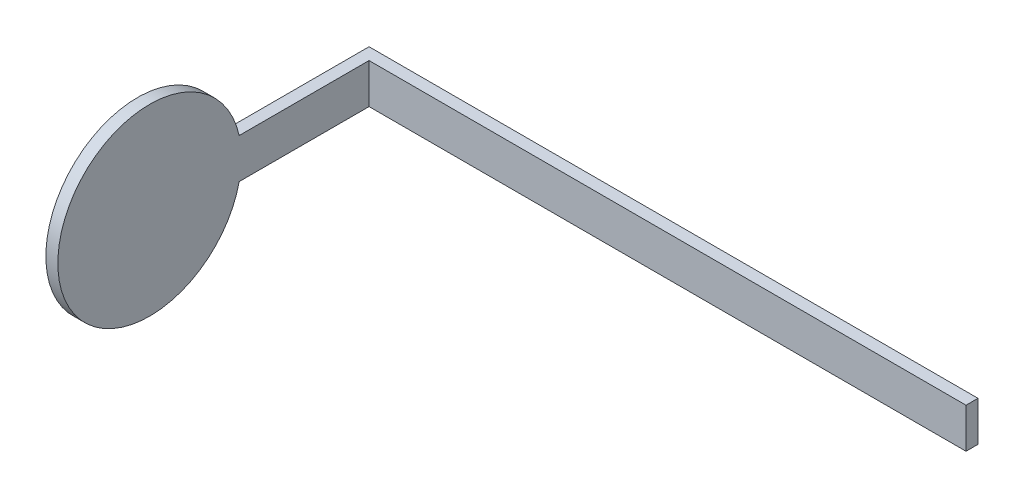
SolidWorks part; units mm, degrees
ref_plane "Спереди" through (0, 0, 0) normal (0, 0, 1) x (1, 0, 0)
ref_plane "Сверху" through (0, 0, 0) normal (0, 1, 0) x (1, 0, 0)
ref_plane "Справа" through (0, 0, 0) normal (1, 0, 0) x (0, 0, -1)
ref_plane "Плоскость4"
sketch "Эскиз1" plane through (0, 0, 0) normal (0, 1, 0) x (-1, 0, 0)
  line L0 (0, 0) -> (0, -3)
  line L1 (0, -3) -> (152.615, -3)
  line L2 (152.615, -3) -> (152.615, 60)
  line L3 (152.615, 60) -> (149.615, 60)
  line L4 (149.615, 60) -> (149.615, 0)
  line L5 (149.615, 0) -> (0, 0)
  dimension "D1" = 149.615
  dimension "D2" = 3
  dimension "D3" = 60
extrude "Выдавливание2" add sketch "Эскиз1" along normal blind 10
sketch "Эскиз2" plane through (-149.615, 0, 0) normal (1, 0, 0) x (0, 0, -1)
  circle A0 centre (-55, 5) radius 23
  dimension "D1" = 46
extrude "Выдавливание3" add sketch "Эскиз2" against normal blind 3
